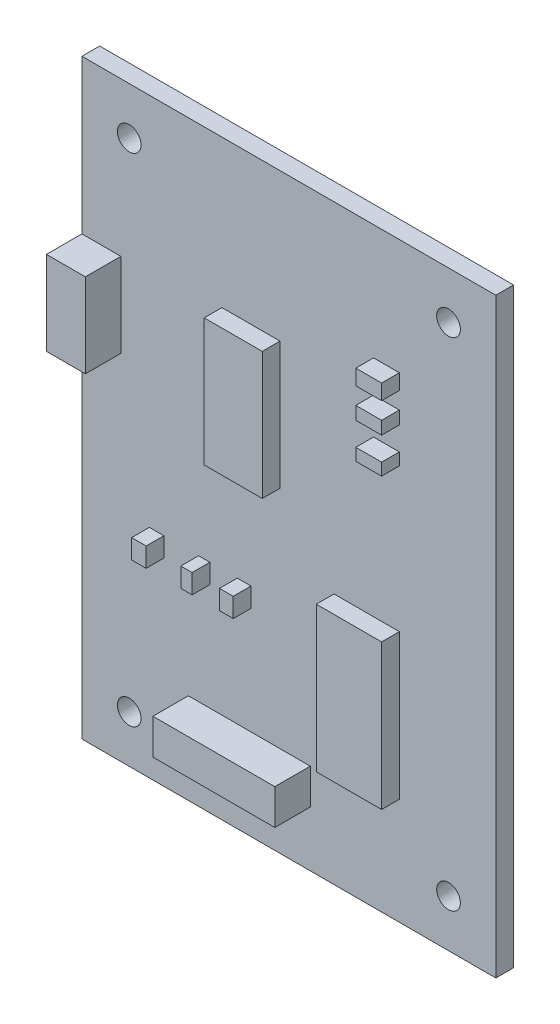
SolidWorks part; units mm, degrees
ref_plane "Спереди" through (0, 0, 0) normal (0, 0, 1) x (1, 0, 0)
ref_plane "Сверху" through (0, 0, 0) normal (0, 1, 0) x (1, 0, 0)
ref_plane "Справа" through (0, 0, 0) normal (1, 0, 0) x (0, 0, -1)
sketch "Эскиз1" plane through (0, 0, 0) normal (0, 0, 1) x (1, 0, 0)
  line L1 (0, 0) -> (70, 0)
  line L2 (0, 0) -> (0, 100)
  line L3 (0, 100) -> (70, 100)
  line L4 (70, 0) -> (70, 100)
  dimension "D1" = 70
  dimension "D2" = 100
extrude "Бобышка-Вытянуть1" add sketch "Эскиз1" along normal blind 3
sketch "Эскиз2" plane through (0, 0, 3) normal (0, 0, 1) x (1, 0, 0)
  line L0 (70, 100) -> (0, 100) construction
  line L1 (0, 100) -> (0, 0) construction
  line L2 (70, 50) -> (0, 50) construction
  line L3 (70, 0) -> (70, 100) construction
  circle A0 centre (8, 92) radius 2
  circle A1 centre (62, 92) radius 2
  circle A2 centre (62, 8) radius 2
  circle A3 centre (8, 8) radius 2
  dimension "D1" = 4
  dimension "D2" = 8
  dimension "D3" = 8
  dimension "D4" = 8
extrude "Вырез-Вытянуть1" cut sketch "Эскиз2" against normal through all
sketch "Эскиз3" plane through (0, 0, 3) normal (0, 0, 1) x (1, 0, 0)
  line L1 (23.68, 75.0266) -> (33.4998, 75.0266)
  line L2 (23.68, 75.0266) -> (23.68, 53.4778)
  line L3 (23.68, 53.4778) -> (33.4998, 53.4778)
  line L4 (33.4998, 75.0266) -> (33.4998, 53.4778)
  line L5 (42.6376, 42.567) -> (53.6847, 42.567)
  line L6 (42.6376, 42.567) -> (42.6376, 18.0177)
  line L7 (42.6376, 18.0177) -> (53.6847, 18.0177)
  line L8 (53.6847, 42.567) -> (53.6847, 18.0177)
  line L9 (11.4054, 36.7025) -> (13.8603, 36.7025)
  line L10 (11.4054, 36.7025) -> (11.4054, 33.4292)
  line L11 (11.4054, 33.4292) -> (13.8603, 33.4292)
  line L12 (13.8603, 36.7025) -> (13.8603, 33.4292)
  line L13 (19.7249, 36.7025) -> (21.6343, 36.7025)
  line L14 (19.7249, 36.7025) -> (19.7249, 33.4292)
  line L15 (19.7249, 33.4292) -> (21.6343, 33.4292)
  line L16 (21.6343, 36.7025) -> (21.6343, 33.4292)
  line L17 (26.2714, 36.7025) -> (28.5899, 36.7025)
  line L18 (26.2714, 36.7025) -> (26.2714, 33.4292)
  line L19 (26.2714, 33.4292) -> (28.5899, 33.4292)
  line L20 (28.5899, 36.7025) -> (28.5899, 33.4292)
  line L21 (49.3204, 68.8893) -> (53.6847, 68.8893)
  line L22 (49.3204, 68.8893) -> (49.3204, 66.8435)
  line L23 (49.3204, 66.8435) -> (53.6847, 66.8435)
  line L24 (53.6847, 68.8893) -> (53.6847, 66.8435)
  line L25 (49.3204, 75.0266) -> (53.6847, 75.0266)
  line L26 (49.3204, 75.0266) -> (49.3204, 72.8445)
  line L27 (49.3204, 72.8445) -> (53.6847, 72.8445)
  line L28 (53.6847, 75.0266) -> (53.6847, 72.8445)
  line L29 (49.3204, 80.482) -> (53.6847, 80.482)
  line L30 (49.3204, 80.482) -> (49.3204, 77.8907)
  line L31 (49.3204, 77.8907) -> (53.6847, 77.8907)
  line L32 (53.6847, 80.482) -> (53.6847, 77.8907)
extrude "Бобышка-Вытянуть2" add sketch "Эскиз3" along normal blind 3
sketch "Эскиз4" plane through (0, 0, 3) normal (0, 0, 1) x (1, 0, 0)
  line L0 (0, 100) -> (0, 0) construction
  line L1 (0, 73.9849) -> (6.5823, 73.9849)
  line L2 (0, 73.9849) -> (0, 59.776)
  line L3 (0, 59.776) -> (6.5823, 59.776)
  line L4 (6.5823, 73.9849) -> (6.5823, 59.776)
  line L6 (18.0051, 15.3385) -> (38.6219, 15.3385)
  line L7 (18.0051, 15.3385) -> (18.0051, 9.3485)
  line L8 (18.0051, 9.3485) -> (38.6219, 9.3485)
  line L9 (38.6219, 15.3385) -> (38.6219, 9.3485)
extrude "Бобышка-Вытянуть3" add sketch "Эскиз4" along normal blind 6
